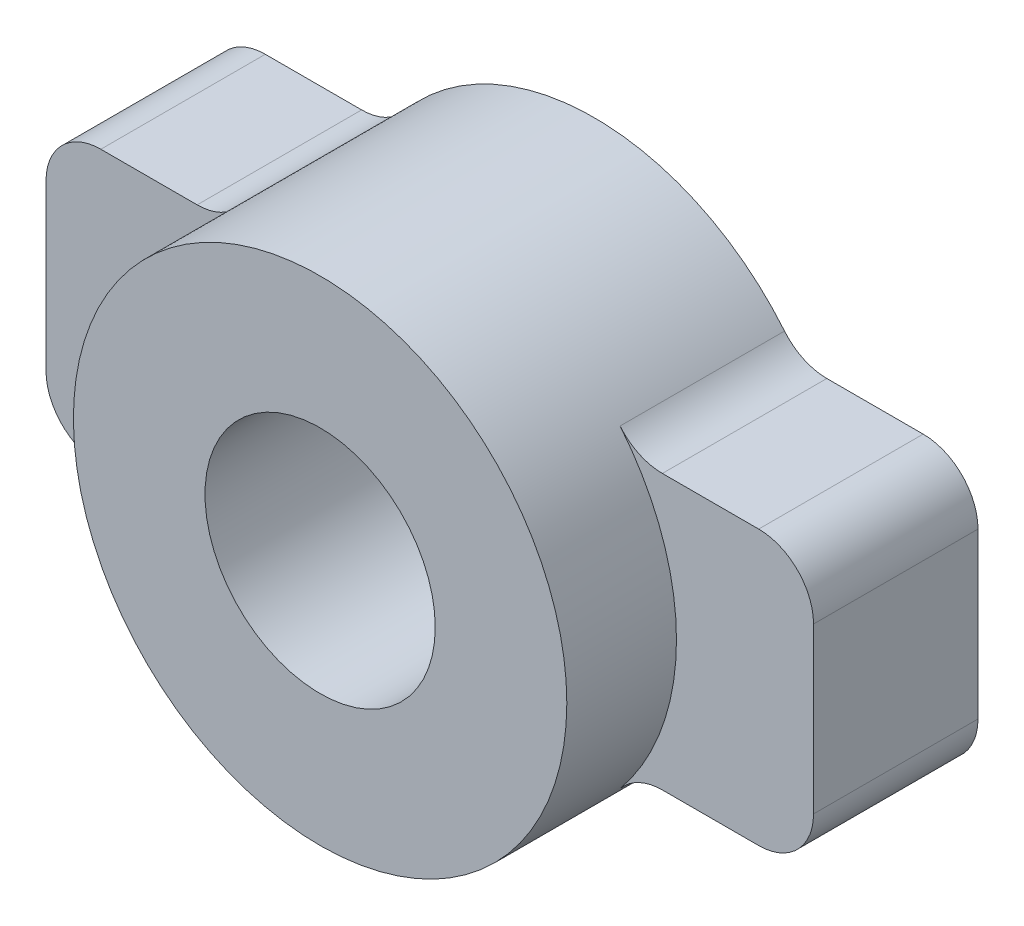
SolidWorks part; units mm, degrees
material "6061 合金"
ref_plane "前视基准面" through (0, 0, 0) normal (0, 0, 1) x (1, 0, 0)
ref_plane "上视基准面" through (0, 0, 0) normal (0, 1, 0) x (1, 0, 0)
ref_plane "右视基准面" through (0, 0, 0) normal (1, 0, 0) x (0, 0, -1)
sketch "草图1" plane through (0, 0, 0) normal (0, 0, 1) x (1, 0, 0)
  circle A0 centre (0, 0) radius 4.5
  dimension "D1" = 9
extrude "凸台-拉伸1" add sketch "草图1" along normal blind 5
sketch "草图2" plane through (0, 0, 0) normal (0, 0, -1) x (-1, 0, 0)
  line L1 (-7, -2.5) -> (7, -2.5)
  line L2 (-7, -2.5) -> (-7, 2.5)
  line L3 (-7, 2.5) -> (7, 2.5)
  line L4 (7, -2.5) -> (7, 2.5)
  line L5 (0, 2.5) -> (0, -2.5) construction
  line L6 (-7, 0) -> (7, 0) construction
  point P0 (0, 0)
  dimension "D1" = 14
  dimension "D2" = 5
extrude "凸台-拉伸2" add sketch "草图2" against normal blind 3
hole_wizard "M5 螺纹孔1" positions "草图3" profile "草图4" tap size "M5" standard "GB" end condition up to next
sketch "草图3" plane through (0, 0, 5) normal (0, 0, 1) x (1, 0, 0)
  point P0 (0, 0)
sketch "草图4" plane through (0, 0, 5) normal (1, 0, 0) x (0, -1, 0)
  line L0 (0, 0) -> (0, 5)
  line L1 (0, 5) -> (2.1, 5)
  line L2 (2.1, 5) -> (2.1, 0)
  line L5 (2.1, 0) -> (0, 0)
  line L11 (0, -6.35) -> (0, 107.95) construction
  dimension "通孔螺纹孔钻头直径" = 4.2
  dimension "通孔螺纹孔钻头深度" = 5
cosmetic thread "孔螺蚊线1" parameters "D2"=5
fillet "圆角1" radius 1 8 edges at (3.7417, 2.5, 1.5) (-3.7417, 2.5, 1.5) (-7, 2.5, 1.5) (-7, -2.5, 1.5) (-3.7417, -2.5, 1.5) (3.7417, -2.5, 1.5) (7, 2.5, 1.5) (7, -2.5, 1.5)
